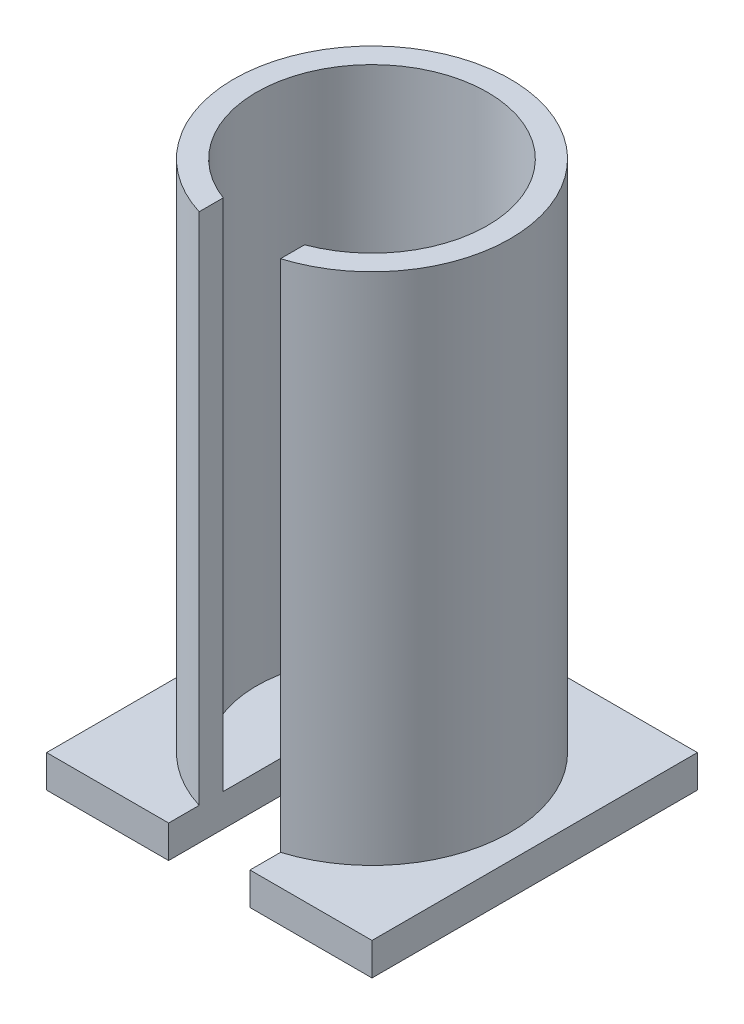
SolidWorks part; units mm, degrees
ref_plane "Front Plane" through (0, 0, 0) normal (0, 0, 1) x (1, 0, 0)
ref_plane "Top Plane" through (0, 0, 0) normal (0, 1, 0) x (1, 0, 0)
ref_plane "Right Plane" through (0, 0, 0) normal (1, 0, 0) x (0, 0, -1)
sketch "Sketch1" plane through (0, 0, 0) normal (0, 1, 0) x (1, 0, 0)
  line L0 (0, 0) -> (0, -4.25)
  circle A0 centre (0, 0) radius 4.25
  circle A1 centre (0, 0) radius 3.55
  dimension "D1" = 8.5
  dimension "D2" = 7.1
extrude "Boss-Extrude1" add sketch "Sketch1" along normal blind 16.8
sketch "Sketch2" plane through (0, 0, 0) normal (0, 1, 0) x (1, 0, 0)
  circle A0 centre (0, 0) radius 3.55
  circle A1 centre (0, 0) radius 1.25
  dimension "D1" = 7.1
  dimension "D2" = 2.5
extrude "Boss-Extrude2" add sketch "Sketch2" along normal blind 1
sketch "Sketch3" plane through (0, 0, 0) normal (0, 1, 0) x (1, 0, 0)
  line L0 (-1.25, 0) -> (1.25, 0)
  line L1 (-1.25, 0) -> (-1.25, -5.0723)
  line L2 (1.25, 0) -> (1.25, -5.0723)
  line L3 (-1.25, -5.0723) -> (1.25, -5.0723)
  circle A0 centre (0, 0) radius 1.25
extrude "Cut-Extrude1" cut sketch "Sketch3" along normal blind 18 contours A0 L1 L3 L2
sketch "Sketch4" plane through (0, 0, 0) normal (0, 1, 0) x (1, 0, 0)
  line L0 (-1.25, 0) -> (1.25, 0)
  line L1 (5, -5) -> (-5, -5)
  line L2 (5, -5) -> (5, 5)
  line L3 (5, 5) -> (-5, 5)
  line L4 (-5, -5) -> (-5, 5)
  line L5 (5, -5) -> (-5, 5) construction
  line L6 (5, 5) -> (-5, -5) construction
  line L7 (-1.25, 0) -> (-1.25, -6.498)
  line L8 (1.25, 0) -> (1.25, -6.498)
  line L9 (-1.25, -6.498) -> (1.25, -6.498)
  circle A0 centre (0, 0) radius 1.25
  point P0 (0, 0)
  dimension "D3" = 2.5
  dimension "D1" = 10
  dimension "D2" = 10
extrude "Boss-Extrude3" add sketch "Sketch4" along normal blind 1 contours A0 L8 L1 L2 L3 L4 L7
